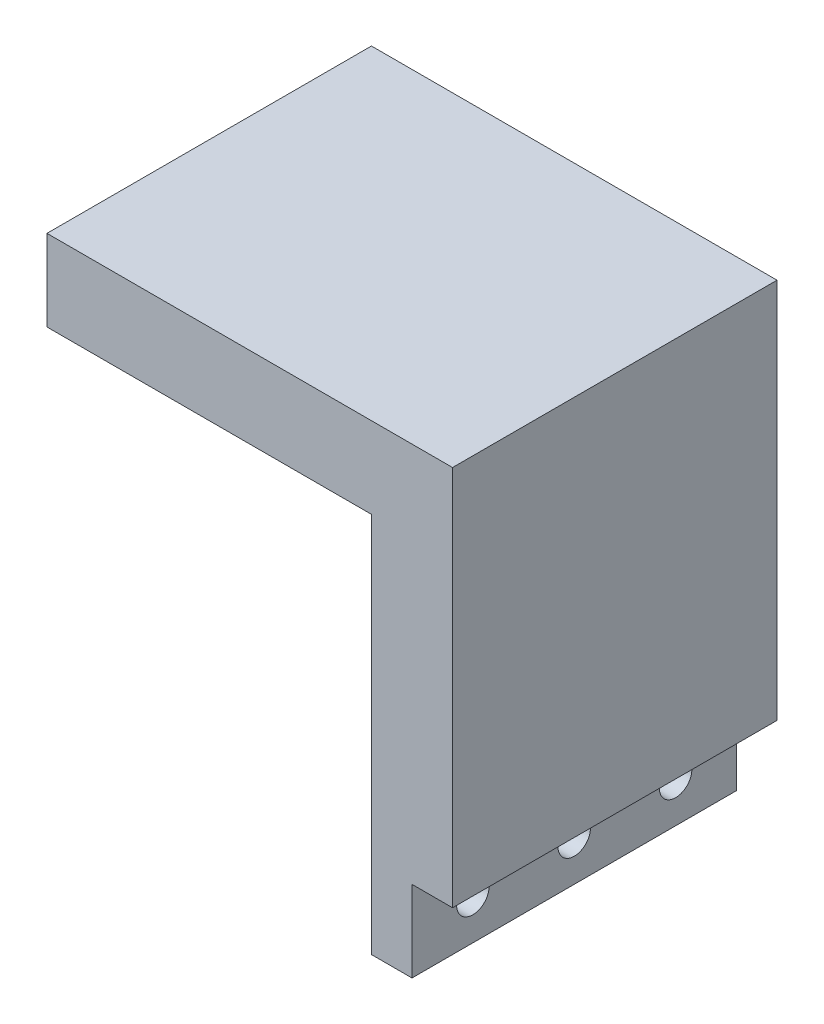
SolidWorks part; units mm, degrees
ref_plane "Front Plane" through (0, 0, 0) normal (0, 0, 1) x (1, 0, 0)
ref_plane "Top Plane" through (0, 0, 0) normal (0, 1, 0) x (1, 0, 0)
ref_plane "Right Plane" through (0, 0, 0) normal (1, 0, 0) x (0, 0, -1)
sketch "Sketch1" plane through (0, 0, 0) normal (0, 0, 1) x (1, 0, 0)
  line L0 (0, 0) -> (0, 87)
  line L1 (0, 87) -> (-50, 87)
  line L2 (-50, 87) -> (-50, 77)
  line L3 (-50, 77) -> (-10, 77)
  line L4 (-10, 77) -> (-10, 0)
  line L5 (-10, 0) -> (0, 0)
  dimension "D1" = 10
  dimension "D2" = 10
  dimension "D3" = 87
  dimension "D4" = 50
extrude "Boss-Extrude1" add sketch "Sketch1" along normal mid plane 40
sketch "Sketch2" plane through (-10, 0, 0) normal (-1, 0, 0) x (0, 0, 1)
  line L1 (-5.6569, 5.3431) -> (5.6569, 5.3431) construction
  line L2 (-5.6569, 5.3431) -> (-5.6569, 16.6569) construction
  line L3 (-5.6569, 16.6569) -> (5.6569, 16.6569) construction
  line L4 (5.6569, 5.3431) -> (5.6569, 16.6569) construction
  line L5 (-5.6569, 5.3431) -> (5.6569, 16.6569) construction
  line L6 (-5.6569, 16.6569) -> (5.6569, 5.3431) construction
  circle A0 centre (0, 11) radius 5.1
  circle A2 centre (5.6569, 16.6569) radius 1.75
  circle A3 centre (5.6569, 5.3431) radius 1.75
  circle A4 centre (-5.6569, 16.6569) radius 1.75
  circle A5 centre (-5.6569, 5.3431) radius 1.75
  dimension "D1" = 10.2
  dimension "D3" = 16
  dimension "D4" = 3.5
  dimension "D2" = 11
extrude "Cut-Extrude1" cut sketch "Sketch2" against normal through all contours A0 | A2 | A4 | A5 | A3
sketch "Sketch3" plane through (0, 0, 20) normal (0, 0, 1) x (1, 0, 0)
  line L0 (-10, 77) -> (-10, 0) construction
  line L1 (0, 0) -> (-10, 0)
  line L2 (0, 0) -> (0, 40)
  line L4 (-10, 0) -> (-10, 30)
  line L5 (-5, 30) -> (-5, 40)
  line L6 (-5, 40) -> (0, 40)
  line L7 (0, 0) -> (0, 87) construction
  line L8 (-10, 30) -> (-5, 30)
  dimension "D1" = 40
  dimension "D2" = 10
extrude "Cut-Extrude2" cut sketch "Sketch3" against normal through all
hole_wizard "Ø4.0 (4) Diameter Hole1" positions "Sketch4" profile "Sketch5" hole size "Ø4.0" standard "ISO" end condition through all
sketch "Sketch4" plane through (-5, 0, 0) normal (1, 0, 0) x (0, 0, -1)
  line L0 (20, 30) -> (-20, 30) construction
  line L1 (0, 69.4645) -> (0, -4.3051) construction
  point P0 (-12.5, 35)
  point P2 (0, 35)
  point P4 (12.5, 35)
  dimension "D1" = 5
  dimension "D2" = 25
sketch "Sketch5" plane through (-5, 35, 12.5) normal (0, 1, 0) x (0, 0, -1)
  line L0 (0, 0) -> (0, 45)
  line L1 (0, 45) -> (2, 45)
  line L2 (2, 45) -> (2, 0)
  line L5 (2, 0) -> (0, 0)
  line L11 (0, -6.35) -> (0, 107.95) construction
  dimension "Thru Hole Dia." = 4
  dimension "Thru Hole Depth" = 45
